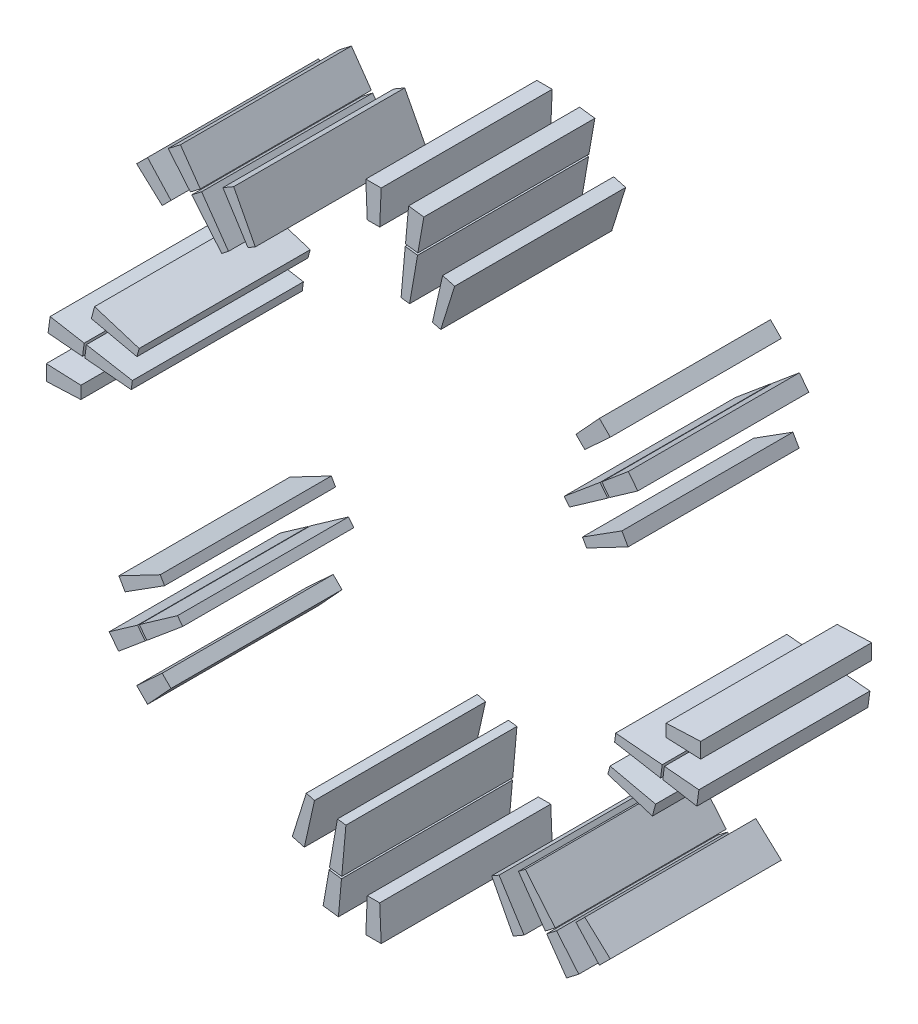
SolidWorks part; units mm, degrees
ref_plane "Спереди" through (0, 0, 0) normal (0, 0, 1) x (1, 0, 0)
ref_plane "Сверху" through (0, 0, 0) normal (0, 1, 0) x (1, 0, 0)
ref_plane "Справа" through (0, 0, 0) normal (1, 0, 0) x (0, 0, -1)
sketch "Эскиз1" plane through (0, 0, 0) normal (0, 0, 1) x (1, 0, 0)
  line L0 (51.3269, -1.0918) -> (57.3923, -1.35)
  line L1 (57.3923, -1.35) -> (57.3923, 1.35)
  line L2 (57.3923, 1.35) -> (51.3269, 1.0918)
  line L3 (51.3269, 1.0918) -> (51.3269, -1.0918)
  line L4 (37.4019, 20.728) -> (44.6599, 24.5237)
  line L5 (44.6599, 24.5237) -> (43.5681, 26.4148)
  line L6 (43.5681, 26.4148) -> (36.6519, 22.027)
  line L7 (36.6519, 22.027) -> (37.4019, 20.728)
  line L8 (41.385, 30.3796) -> (46.3542, 33.8672)
  line L9 (46.3542, 33.8672) -> (44.7106, 36.0093)
  line L10 (44.7106, 36.0093) -> (40.0557, 32.112)
  line L11 (40.0557, 32.112) -> (41.385, 30.3796)
  line L12 (34.3764, 25.4326) -> (41.0769, 30.1432)
  line L13 (41.0769, 30.1432) -> (39.7475, 31.8756)
  line L14 (39.7475, 31.8756) -> (33.4632, 26.6226)
  line L15 (33.4632, 26.6226) -> (34.3764, 25.4326)
  line L16 (37.0656, 35.5215) -> (41.5371, 39.6279)
  line L17 (41.5371, 39.6279) -> (39.6279, 41.5371)
  line L18 (39.6279, 41.5371) -> (35.5215, 37.0656)
  line L19 (35.5215, 37.0656) -> (37.0656, 35.5215)
  line L20 (11.7902, 41.104) -> (14.2385, 48.9202)
  line L21 (14.2385, 48.9202) -> (12.1292, 49.4854)
  line L22 (12.1292, 49.4854) -> (10.3414, 41.4922)
  line L23 (10.3414, 41.4922) -> (11.7902, 41.104)
  line L24 (7.782, 50.7452) -> (8.8296, 56.7251)
  line L25 (8.8296, 56.7251) -> (6.1527, 57.0775)
  line L26 (6.1527, 57.0775) -> (5.617, 51.0303)
  line L27 (5.617, 51.0303) -> (7.782, 50.7452)
  line L28 (6.3242, 42.2913) -> (7.7313, 50.3602)
  line L29 (7.7313, 50.3602) -> (5.5663, 50.6452)
  line L30 (5.5663, 50.6452) -> (4.8371, 42.4871)
  line L31 (4.8371, 42.4871) -> (6.3242, 42.2913)
  line L32 (1.0918, 51.3269) -> (1.35, 57.3923)
  line L33 (1.35, 57.3923) -> (-1.35, 57.3923)
  line L34 (-1.35, 57.3923) -> (-1.0918, 51.3269)
  line L35 (-1.0918, 51.3269) -> (1.0918, 51.3269)
  line L36 (-20.728, 37.4019) -> (-24.5237, 44.6599)
  line L37 (-24.5237, 44.6599) -> (-26.4148, 43.5681)
  line L38 (-26.4148, 43.5681) -> (-22.027, 36.6519)
  line L39 (-22.027, 36.6519) -> (-20.728, 37.4019)
  line L40 (-30.3796, 41.385) -> (-33.8672, 46.3542)
  line L41 (-33.8672, 46.3542) -> (-36.0093, 44.7106)
  line L42 (-36.0093, 44.7106) -> (-32.112, 40.0557)
  line L43 (-32.112, 40.0557) -> (-30.3796, 41.385)
  line L44 (-25.4326, 34.3764) -> (-30.1432, 41.0769)
  line L45 (-30.1432, 41.0769) -> (-31.8756, 39.7475)
  line L46 (-31.8756, 39.7475) -> (-26.6226, 33.4632)
  line L47 (-26.6226, 33.4632) -> (-25.4326, 34.3764)
  line L48 (-35.5215, 37.0656) -> (-39.6279, 41.5371)
  line L49 (-39.6279, 41.5371) -> (-41.5371, 39.6279)
  line L50 (-41.5371, 39.6279) -> (-37.0656, 35.5215)
  line L51 (-37.0656, 35.5215) -> (-35.5215, 37.0656)
  line L52 (-41.104, 11.7902) -> (-48.9202, 14.2385)
  line L53 (-48.9202, 14.2385) -> (-49.4854, 12.1292)
  line L54 (-49.4854, 12.1292) -> (-41.4922, 10.3414)
  line L55 (-41.4922, 10.3414) -> (-41.104, 11.7902)
  line L56 (-50.7452, 7.782) -> (-56.7251, 8.8296)
  line L57 (-56.7251, 8.8296) -> (-57.0775, 6.1527)
  line L58 (-57.0775, 6.1527) -> (-51.0303, 5.617)
  line L59 (-51.0303, 5.617) -> (-50.7452, 7.782)
  line L60 (-42.2913, 6.3242) -> (-50.3602, 7.7313)
  line L61 (-50.3602, 7.7313) -> (-50.6452, 5.5663)
  line L62 (-50.6452, 5.5663) -> (-42.4871, 4.8371)
  line L63 (-42.4871, 4.8371) -> (-42.2913, 6.3242)
  line L64 (-51.3269, 1.0918) -> (-57.3923, 1.35)
  line L65 (-57.3923, 1.35) -> (-57.3923, -1.35)
  line L66 (-57.3923, -1.35) -> (-51.3269, -1.0918)
  line L67 (-51.3269, -1.0918) -> (-51.3269, 1.0918)
  line L68 (-37.4019, -20.728) -> (-44.6599, -24.5237)
  line L69 (-44.6599, -24.5237) -> (-43.5681, -26.4148)
  line L70 (-43.5681, -26.4148) -> (-36.6519, -22.027)
  line L71 (-36.6519, -22.027) -> (-37.4019, -20.728)
  line L72 (-41.385, -30.3796) -> (-46.3542, -33.8672)
  line L73 (-46.3542, -33.8672) -> (-44.7106, -36.0093)
  line L74 (-44.7106, -36.0093) -> (-40.0557, -32.112)
  line L75 (-40.0557, -32.112) -> (-41.385, -30.3796)
  line L76 (-34.3764, -25.4326) -> (-41.0769, -30.1432)
  line L77 (-41.0769, -30.1432) -> (-39.7475, -31.8756)
  line L78 (-39.7475, -31.8756) -> (-33.4632, -26.6226)
  line L79 (-33.4632, -26.6226) -> (-34.3764, -25.4326)
  line L80 (-37.0656, -35.5215) -> (-41.5371, -39.6279)
  line L81 (-41.5371, -39.6279) -> (-39.6279, -41.5371)
  line L82 (-39.6279, -41.5371) -> (-35.5215, -37.0656)
  line L83 (-35.5215, -37.0656) -> (-37.0656, -35.5215)
  line L84 (-11.7902, -41.104) -> (-14.2385, -48.9202)
  line L85 (-14.2385, -48.9202) -> (-12.1292, -49.4854)
  line L86 (-12.1292, -49.4854) -> (-10.3414, -41.4922)
  line L87 (-10.3414, -41.4922) -> (-11.7902, -41.104)
  line L88 (-7.782, -50.7452) -> (-8.8296, -56.7251)
  line L89 (-8.8296, -56.7251) -> (-6.1527, -57.0775)
  line L90 (-6.1527, -57.0775) -> (-5.617, -51.0303)
  line L91 (-5.617, -51.0303) -> (-7.782, -50.7452)
  line L92 (-6.3242, -42.2913) -> (-7.7313, -50.3602)
  line L93 (-7.7313, -50.3602) -> (-5.5663, -50.6452)
  line L94 (-5.5663, -50.6452) -> (-4.8371, -42.4871)
  line L95 (-4.8371, -42.4871) -> (-6.3242, -42.2913)
  line L96 (-1.0918, -51.3269) -> (-1.35, -57.3923)
  line L97 (-1.35, -57.3923) -> (1.35, -57.3923)
  line L98 (1.35, -57.3923) -> (1.0918, -51.3269)
  line L99 (1.0918, -51.3269) -> (-1.0918, -51.3269)
  line L100 (20.728, -37.4019) -> (24.5237, -44.6599)
  line L101 (24.5237, -44.6599) -> (26.4148, -43.5681)
  line L102 (26.4148, -43.5681) -> (22.027, -36.6519)
  line L103 (22.027, -36.6519) -> (20.728, -37.4019)
  line L104 (30.3796, -41.385) -> (33.8672, -46.3542)
  line L105 (33.8672, -46.3542) -> (36.0093, -44.7106)
  line L106 (36.0093, -44.7106) -> (32.112, -40.0557)
  line L107 (32.112, -40.0557) -> (30.3796, -41.385)
  line L108 (25.4326, -34.3764) -> (30.1432, -41.0769)
  line L109 (30.1432, -41.0769) -> (31.8756, -39.7475)
  line L110 (31.8756, -39.7475) -> (26.6226, -33.4632)
  line L111 (26.6226, -33.4632) -> (25.4326, -34.3764)
  line L112 (35.5215, -37.0656) -> (39.6279, -41.5371)
  line L113 (39.6279, -41.5371) -> (41.5371, -39.6279)
  line L114 (41.5371, -39.6279) -> (37.0656, -35.5215)
  line L115 (37.0656, -35.5215) -> (35.5215, -37.0656)
  line L116 (41.104, -11.7902) -> (48.9202, -14.2385)
  line L117 (48.9202, -14.2385) -> (49.4854, -12.1292)
  line L118 (49.4854, -12.1292) -> (41.4922, -10.3414)
  line L119 (41.4922, -10.3414) -> (41.104, -11.7902)
  line L120 (50.7452, -7.782) -> (56.7251, -8.8296)
  line L121 (56.7251, -8.8296) -> (57.0775, -6.1527)
  line L122 (57.0775, -6.1527) -> (51.0303, -5.617)
  line L123 (51.0303, -5.617) -> (50.7452, -7.782)
  line L124 (42.2913, -6.3242) -> (50.3602, -7.7313)
  line L125 (50.3602, -7.7313) -> (50.6452, -5.5663)
  line L126 (50.6452, -5.5663) -> (42.4871, -4.8371)
  line L127 (42.4871, -4.8371) -> (42.2913, -6.3242)
extrude "Slot_copper_envelopes" add sketch "Эскиз1" along normal blind 30 from offset 15 separate body
